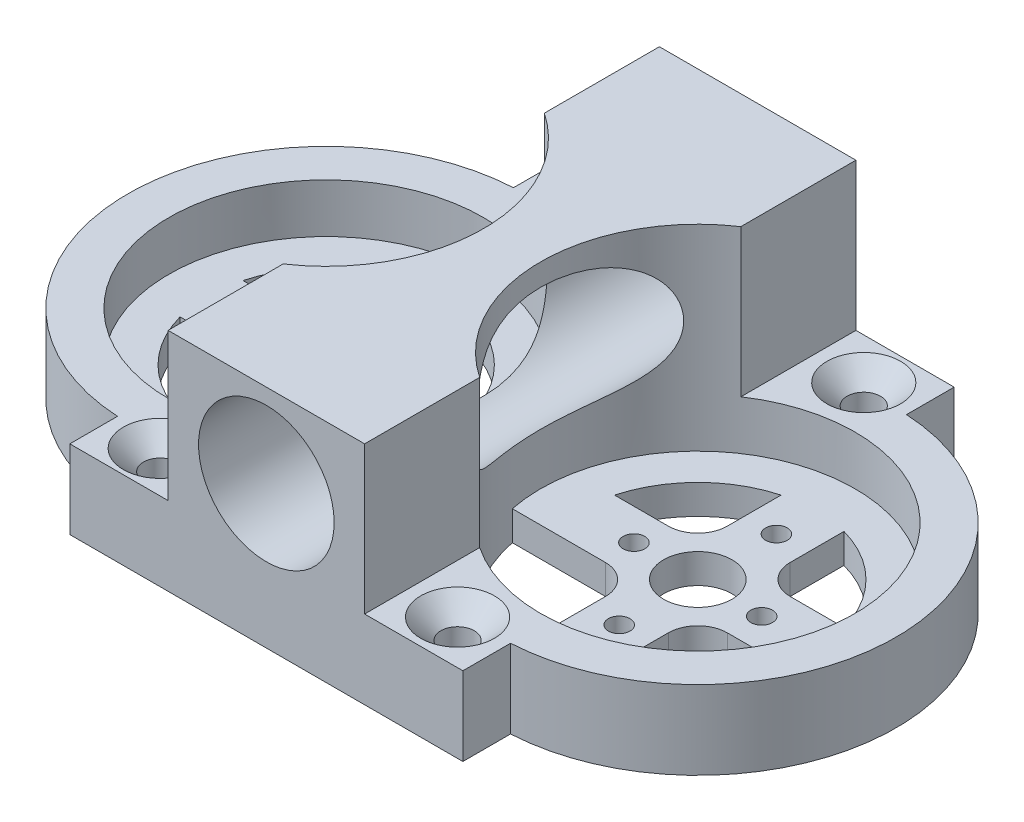
SolidWorks part; units mm, degrees
ref_plane "Front Plane" through (0, 0, 0) normal (0, 0, 1) x (1, 0, 0)
ref_plane "Top Plane" through (0, 0, 0) normal (0, 1, 0) x (1, 0, 0)
ref_plane "Right Plane" through (0, 0, 0) normal (1, 0, 0) x (0, 0, -1)
sketch "Sketch1" plane through (0, 0, 0) normal (0, 1, 0) x (1, 0, 0)
  line L0 (-6.9348, 40.7645) -> (-6.9348, -29.2355) construction
  line L1 (-13.4348, 40.7645) -> (-0.4348, 40.7645) construction
  line L2 (-13.4348, 40.7645) -> (-13.4348, -29.2355) construction
  line L3 (-13.4348, -29.2355) -> (-0.4348, -29.2355) construction
  line L4 (-0.4348, 40.7645) -> (-0.4348, -29.2355) construction
  circle A0 centre (-25.8448, 2.7176) radius 16 construction
  circle A1 centre (-25.8448, 2.7176) radius 12.105 construction
  circle A2 centre (11.9752, 2.7176) radius 16 construction
  circle A3 centre (11.9752, 2.7176) radius 12.105 construction
  dimension "D1" = 32
  dimension "D2" = 24.21
  dimension "D3" = 37.82
  dimension "D4" = 13
  dimension "D5" = 70
  dimension "D6" = 18.91
sketch "Sketch2" plane through (0, 0, 0) normal (0, 1, 0) x (1, 0, 0)
  line L0 (-26.9348, -17.4307) -> (-26.9348, -22.2824)
  line L1 (-26.9348, 27.7176) -> (13.0652, 27.7176)
  line L2 (-26.9348, 27.7176) -> (-26.9348, 22.866)
  line L3 (-26.9348, -22.2824) -> (13.0652, -22.2824)
  line L4 (13.0652, 27.7176) -> (13.0652, 22.866)
  line L5 (13.0652, -17.4307) -> (13.0652, -22.2824)
  line L6 (-6.9348, 40.7645) -> (-6.9348, -29.2355) construction
  line L7 (-6.9348, -22.2824) -> (-6.9348, 42.9295) construction
  arc A0 (-26.9348, 22.866) -> (-26.9348, -17.4307) centre (-25.8448, 2.7176) ccw
  arc A1 (13.0652, -17.4307) -> (13.0652, 22.866) centre (11.9752, 2.7176) ccw
  dimension "D1" = 40
  dimension "D3" = 20.1778
  dimension "D2" = 50
  dimension "D4" = 37.82
  dimension "D5" = 25
  dimension "D6" = 20
  dimension "D7" = 40
  dimension "D8" = 20
extrude "Boss-Extrude1" add sketch "Sketch2" along normal blind 8
sketch "Sketch4" plane through (0, 8, 0) normal (0, 1, 0) x (1, 0, 0)
  circle A0 centre (-25.8448, 2.7176) radius 16
  circle A1 centre (11.9752, 2.7176) radius 16
  dimension "D1" = 32
  dimension "D2" = 32
extrude "Cut-Extrude1" cut sketch "Sketch4" against normal blind 5
sketch "Sketch6" plane through (0, 3, 0) normal (0, 1, 0) x (1, 0, 0)
  line L0 (-29.0448, -3.4824) -> (-29.0448, -8.9567)
  line L1 (-32.0448, -0.4824) -> (-37.5192, -0.4824)
  line L2 (-29.0448, 8.9176) -> (-29.0448, 14.392)
  line L3 (-32.0448, 5.9176) -> (-37.5192, 5.9176)
  line L4 (-22.6448, 8.9176) -> (-22.6448, 14.392)
  line L5 (-22.6448, -3.4824) -> (-22.6448, -12.9591)
  line L6 (-19.6448, -0.4824) -> (-10.1681, -0.4824)
  line L7 (-19.6448, 5.9176) -> (-14.1704, 5.9176)
  line L8 (-6.9348, 52.7176) -> (-6.9348, -22.2824) construction
  line L11 (-3.7016, -0.4824) -> (5.7752, -0.4824)
  line L12 (0.3008, 5.9176) -> (5.7752, 5.9176)
  line L13 (8.7752, 14.392) -> (8.7752, 8.9176)
  line L14 (15.1752, -8.9567) -> (15.1752, -3.4824)
  line L15 (18.1752, -0.4824) -> (23.6496, -0.4824)
  line L16 (8.7752, -3.4824) -> (8.7752, -12.9591)
  line L17 (18.1752, 5.9176) -> (23.6496, 5.9176)
  line L18 (15.1752, 8.9176) -> (15.1752, 14.392)
  circle A0 centre (-25.8448, 2.7176) radius 6 construction
  circle A1 centre (-25.8448, 2.7176) radius 8 construction
  circle A2 centre (-33.8448, 2.7176) radius 1.1
  circle A3 centre (-17.8448, 2.7176) radius 1.1
  circle A4 centre (-25.8448, 8.7176) radius 1.1
  circle A5 centre (-25.8448, -3.2824) radius 1.1
  circle A6 centre (-25.8448, 2.7176) radius 3.2
  arc A8 (-37.5192, -0.4824) -> (-29.0448, -8.9567) centre (-25.8448, 2.7176) ccw
  arc A9 (-22.6448, -3.4824) -> (-19.6448, -0.4824) centre (-19.6448, -3.4824) cw
  arc A10 (-22.6448, 8.9176) -> (-19.6448, 5.9176) centre (-19.6448, 8.9176) ccw
  arc A11 (-29.0448, 8.9176) -> (-32.0448, 5.9176) centre (-32.0448, 8.9176) cw
  arc A12 (-29.0448, -3.4824) -> (-32.0448, -0.4824) centre (-32.0448, -3.4824) ccw
  arc A13 (-29.0448, 14.392) -> (-37.5192, 5.9176) centre (-25.8448, 2.7176) ccw
  arc A14 (-14.1704, 5.9176) -> (-22.6448, 14.392) centre (-25.8448, 2.7176) ccw
  circle A16 centre (11.9752, 2.7176) radius 6.5 construction
  circle A17 centre (11.9752, 2.7176) radius 8 construction
  arc A19 (23.6496, 5.9176) -> (15.1752, 14.392) centre (11.9752, 2.7176) ccw
  circle A20 centre (18.4752, 2.7176) radius 1.1
  circle A21 centre (11.9752, 10.7176) radius 1.1
  circle A22 centre (5.4752, 2.7176) radius 1.1
  circle A23 centre (11.9752, -5.2824) radius 1.1
  arc A24 (8.7752, 14.392) -> (0.3008, 5.9176) centre (11.9752, 2.7176) ccw
  arc A25 (-22.6448, -12.9591) -> (-10.1681, -0.4824) centre (-25.8448, 2.7176) ccw
  arc A26 (15.1752, -8.9567) -> (23.6496, -0.4824) centre (11.9752, 2.7176) ccw
  arc A27 (18.1752, -0.4824) -> (15.1752, -3.4824) centre (18.1752, -3.4824) ccw
  arc A28 (18.1752, 5.9176) -> (15.1752, 8.9176) centre (18.1752, 8.9176) cw
  arc A29 (8.7752, 8.9176) -> (5.7752, 5.9176) centre (5.7752, 8.9176) cw
  arc A30 (5.7752, -0.4824) -> (8.7752, -3.4824) centre (5.7752, -3.4824) cw
  circle A31 centre (11.9752, 2.7176) radius 3.4812
  arc A33 (-3.7016, -0.4824) -> (8.7752, -12.9591) centre (11.9752, 2.7176) ccw
  point P31 (-22.6448, 5.9176)
  point P36 (-29.0448, -0.4824)
  point P71 (15.1752, 5.9176)
  point P77 (8.7752, -0.4824)
extrude "Cut-Extrude3" cut sketch "Sketch6" against normal up to next
sketch "Sketch8" plane through (0, 8, 0) normal (0, 1, 0) x (1, 0, 0)
  line L0 (13.0652, 27.7176) -> (-26.9348, 27.7176) construction
  line L1 (-16.9348, 27.7176) -> (3.0652, 27.7176)
  line L2 (-16.9348, 27.7176) -> (-16.9348, 16.0072)
  line L3 (-16.9348, -22.2824) -> (3.0652, -22.2824)
  line L4 (3.0652, 27.7176) -> (3.0652, 16.0072)
  line L5 (-26.9348, -22.2824) -> (13.0652, -22.2824) construction
  line L6 (-26.9348, 27.7176) -> (-26.9348, 22.866) construction
  line L7 (-16.9348, -10.5719) -> (-16.9348, -22.2824)
  line L8 (3.0652, -10.5719) -> (3.0652, -22.2824)
  circle A0 centre (-25.8448, 2.7176) radius 16 construction
  arc A1 (-16.9348, -10.5719) -> (-16.9348, 16.0072) centre (-25.8448, 2.7176) ccw
  circle A2 centre (11.9752, 2.7176) radius 16 construction
  arc A3 (3.0652, 16.0072) -> (3.0652, -10.5719) centre (11.9752, 2.7176) ccw
  dimension "D1" = 20
  dimension "D2" = 10
extrude "Boss-Extrude2" add sketch "Sketch8" along normal blind 15
sketch "Sketch7" plane through (0, 0, 22.2824) normal (0, 0, 1) x (1, 0, 0)
  line L1 (-26.9348, 8) -> (-26.9348, 0) construction
  line L2 (-26.9348, 0) -> (13.0652, 0) construction
  circle A0 centre (-6.9348, 14.5) radius 6.9
  dimension "D2" = 13.8
  dimension "D3" = 20
  dimension "D4" = 14.5
extrude "Cut-Extrude4" cut sketch "Sketch7" against normal up to next
hole_wizard "CSK for M3 Countersunk Flat Head Screw1" positions "Sketch10" profile "Sketch9" countersink size "M3" standard "DIN"
sketch "Sketch10" plane through (0, 8, 0) normal (0, 1, 0) x (1, 0, 0)
  line L0 (-6.9348, 27.7176) -> (-6.9348, -22.2824) construction
  line L1 (3.0652, 27.7176) -> (-16.9348, 27.7176) construction
  line L2 (-16.9348, -22.2824) -> (3.0652, -22.2824) construction
  line L4 (-26.9348, -22.2824) -> (-16.9348, -22.2824) construction
  line L5 (-16.9348, 27.7176) -> (-26.9348, 27.7176) construction
  point P0 (8.0652, 23.5176)
  point P2 (-21.9348, 23.5176)
  point P4 (-21.9348, -18.0824)
  point P6 (8.0652, -17.8218)
  dimension "D1" = 15
  dimension "D2" = 15
  dimension "D3" = 4.2
  dimension "D4" = 4.2
sketch "Sketch9" plane through (8.0652, 8, -23.5176) normal (1, 0, 0) x (0, 0, 1)
  line L0 (0, 0) -> (0, 11.0215)
  line L1 (0, 11.0215) -> (1.7, 10)
  line L2 (1.7, 10) -> (1.7, 2.05)
  line L3 (1.7, 2.05) -> (3.75, 0)
  line L5 (3.75, 0) -> (0, 0)
  line L6 (-1.7, 2.05) -> (-3.75, 0) construction
  line L10 (0, 11.0215) -> (-1.7, 10) construction
  line L11 (0, -6.35) -> (0, 107.95) construction
  dimension "Hole Dia." = 3.4
  dimension "Hole Depth" = 10
  dimension "Near C'Sink Dia." = 7.5
  dimension "Near C'Sink Angle" = 90
  dimension "Drill Angle" = 118
